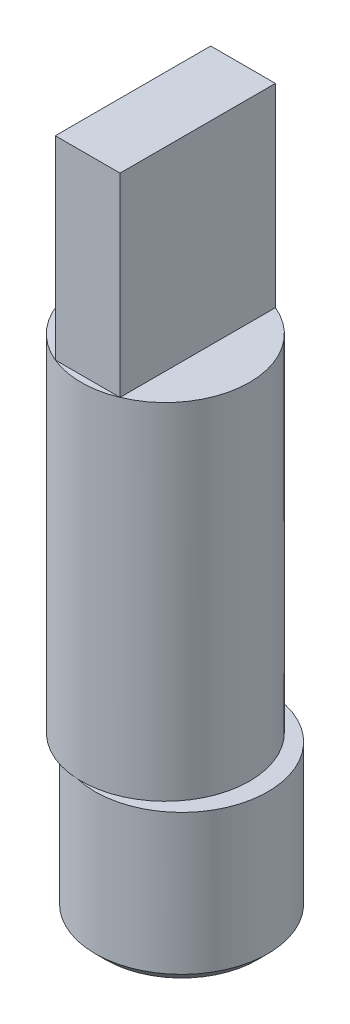
SolidWorks part; units mm, degrees
ref_plane "Front Plane" through (0, 0, 0) normal (0, 0, 1) x (1, 0, 0)
ref_plane "Top Plane" through (0, 0, 0) normal (0, 1, 0) x (1, 0, 0)
ref_plane "Right Plane" through (0, 0, 0) normal (1, 0, 0) x (0, 0, -1)
sketch "Sketch1" plane through (0, 0, 0) normal (0, 1, 0) x (1, 0, 0)
  circle A0 centre (0, 0) radius 4
  dimension "D1" = 8
extrude "Boss-Extrude1" add sketch "Sketch1" along normal blind 7
sketch "Sketch2" plane through (0, 7, 0) normal (0, 1, 0) x (1, 0, 0)
  circle A1 centre (-0.75, 0) radius 3.9
  dimension "D1" = 0.75
extrude "Boss-Extrude2" add sketch "Sketch2" along normal blind 16
chamfer "Chamfer1" distance 0.5 angle 45 1 edges at (0, 0, 4)
sketch "Sketch3" plane through (0, 23, 0) normal (0, 1, 0) x (1, 0, 0)
  line L1 (-2.25, 3.6) -> (0.75, 3.6)
  line L2 (-2.25, 3.6) -> (-2.25, -3.6)
  line L3 (-2.25, -3.6) -> (0.75, -3.6)
  line L4 (0.75, 3.6) -> (0.75, -3.6)
  line L5 (-2.25, 3.6) -> (0.75, -3.6) construction
  line L6 (-2.25, -3.6) -> (0.75, 3.6) construction
  circle A1 centre (-0.75, 0) radius 3.9 construction
  point P0 (-0.75, 0)
  dimension "D1" = 3
extrude "Boss-Extrude3" add sketch "Sketch3" along normal blind 9
